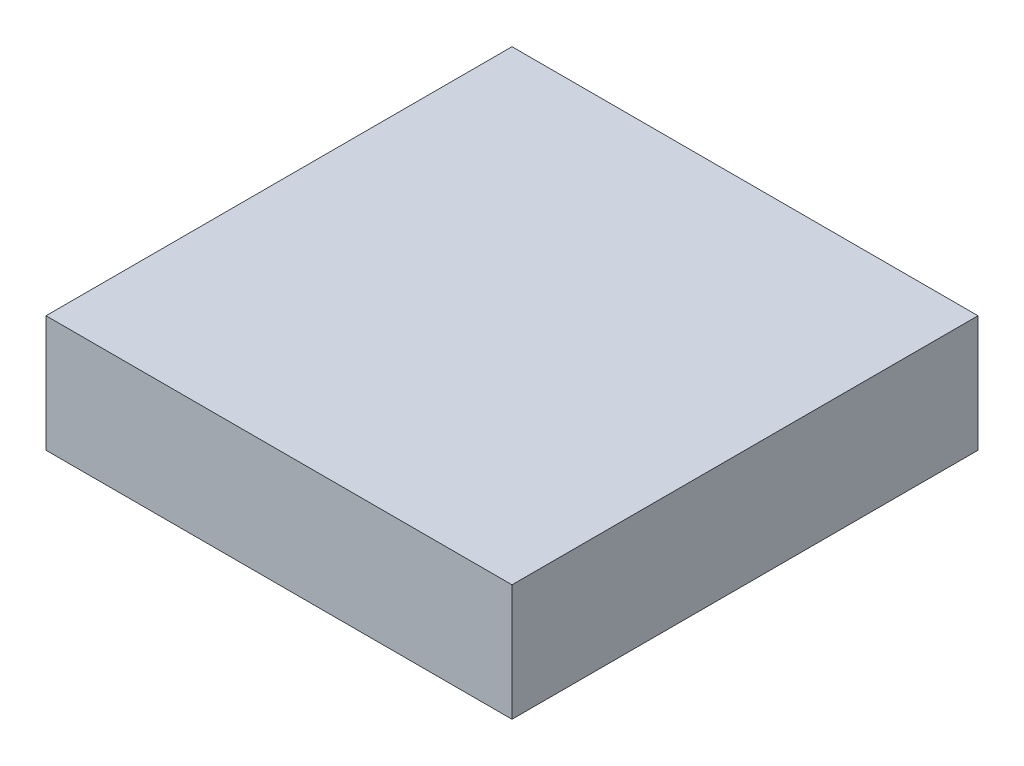
SolidWorks part; units mm, degrees
ref_plane "Front Plane" through (0, 0, 0) normal (0, 0, 1) x (1, 0, 0)
ref_plane "Top Plane" through (0, 0, 0) normal (0, 1, 0) x (1, 0, 0)
ref_plane "Right Plane" through (0, 0, 0) normal (1, 0, 0) x (0, 0, -1)
sketch "Sketch1" plane through (0, 0, 0) normal (0, 1, 0) x (1, 0, 0)
  line L1 (0, 0) -> (3, 0)
  line L2 (0, 0) -> (0, 3)
  line L3 (0, 3) -> (3, 3)
  line L4 (3, 0) -> (3, 3)
  dimension "D1" = 3
  dimension "D2" = 3
extrude "Boss-Extrude1" add sketch "Sketch1" along normal blind 0.75
